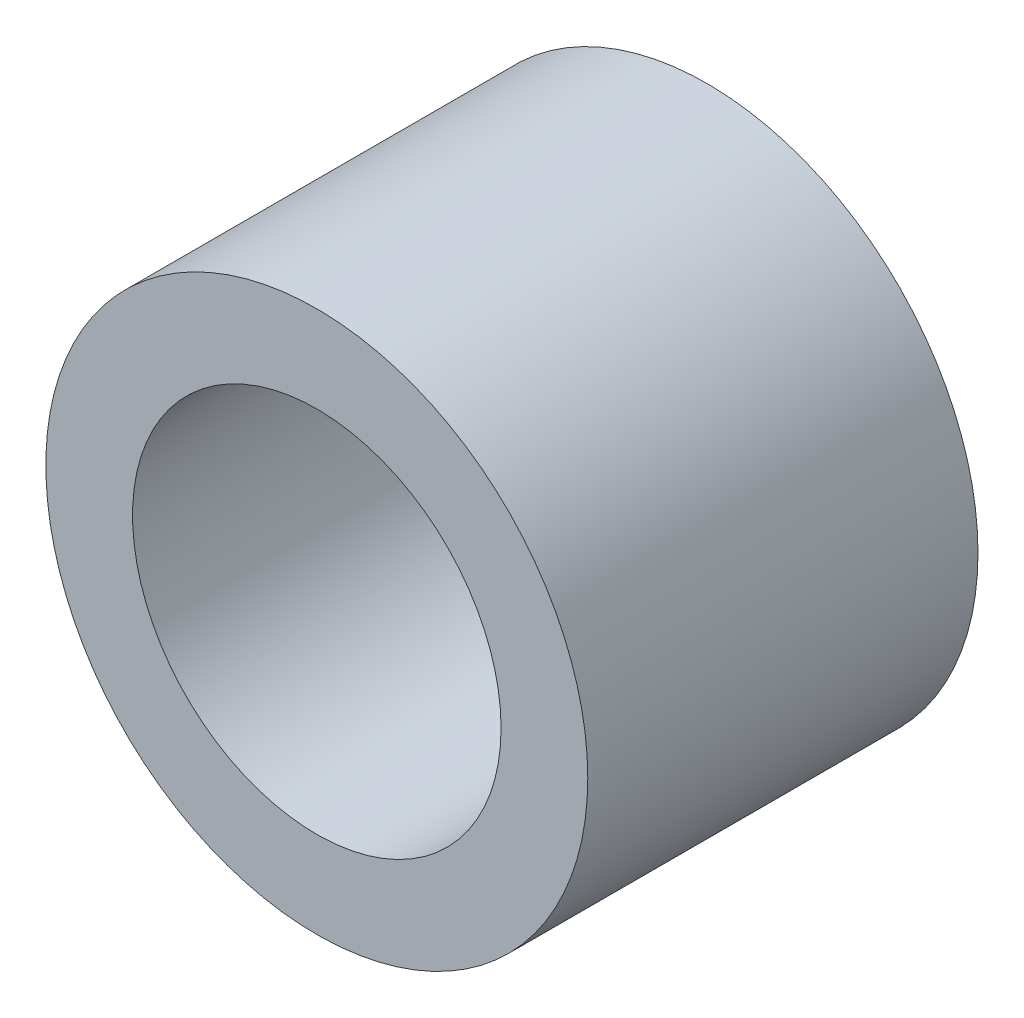
SolidWorks part; units mm, degrees
ref_plane "Front Plane" through (0, 0, 0) normal (0, 0, 1) x (1, 0, 0)
ref_plane "Top Plane" through (0, 0, 0) normal (0, 1, 0) x (1, 0, 0)
ref_plane "Right Plane" through (0, 0, 0) normal (1, 0, 0) x (0, 0, -1)
sketch "Sketch1" plane through (0, 0, 0) normal (0, 0, 1) x (1, 0, 0)
  circle A0 centre (0, 0) radius 3.2385
  circle A1 centre (0, 0) radius 4.7625
extrude "Boss-Extrude1" add sketch "Sketch1" along normal blind 6.858
